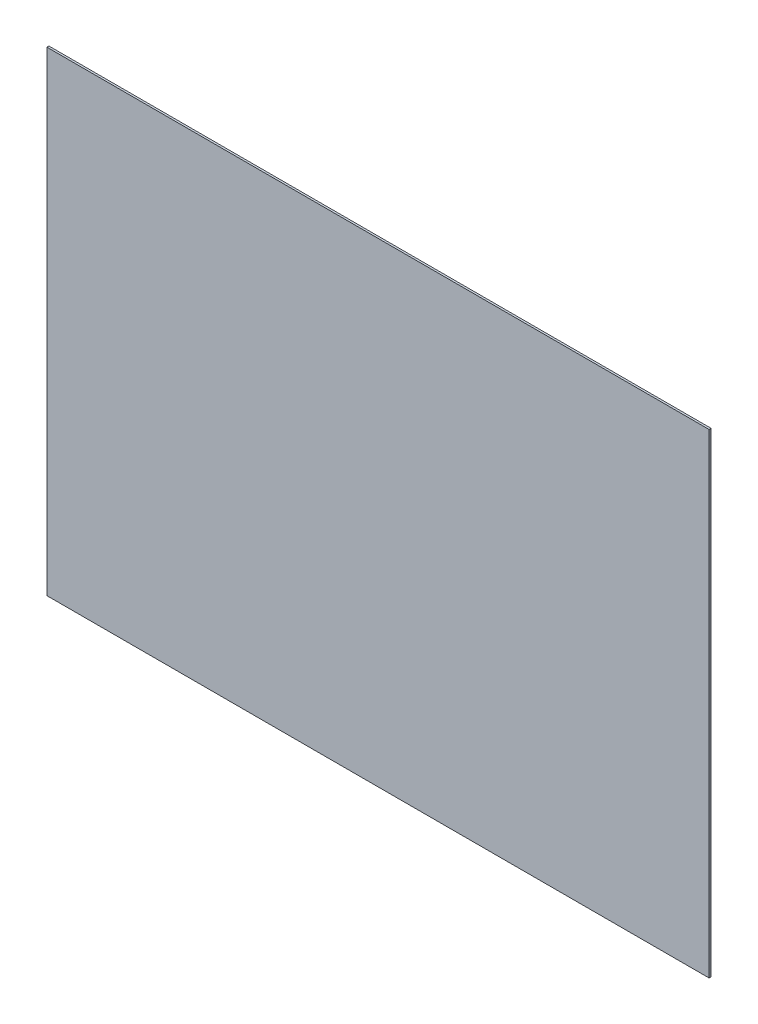
SolidWorks part; units mm, degrees
material "AISI 1020"
ref_plane "Front Plane" through (0, 0, 0) normal (0, 0, 1) x (1, 0, 0)
ref_plane "Top Plane" through (0, 0, 0) normal (0, 1, 0) x (1, 0, 0)
ref_plane "Right Plane" through (0, 0, 0) normal (1, 0, 0) x (0, 0, -1)
sketch "Sketch1" plane through (0, 0, 0) normal (0, 0, 1) x (1, 0, 0)
  line L1 (-247.7, 177.7) -> (247.7, 177.7)
  line L2 (-247.7, 177.7) -> (-247.7, -177.7)
  line L3 (-247.7, -177.7) -> (247.7, -177.7)
  line L4 (247.7, 177.7) -> (247.7, -177.7)
  line L5 (-247.7, 177.7) -> (247.7, -177.7) construction
  line L6 (-247.7, -177.7) -> (247.7, 177.7) construction
  point P0 (0, 0)
  dimension "D1" = 495.4
  dimension "D2" = 355.4
extrude "Boss-Extrude1" add sketch "Sketch1" along normal blind 1.5
